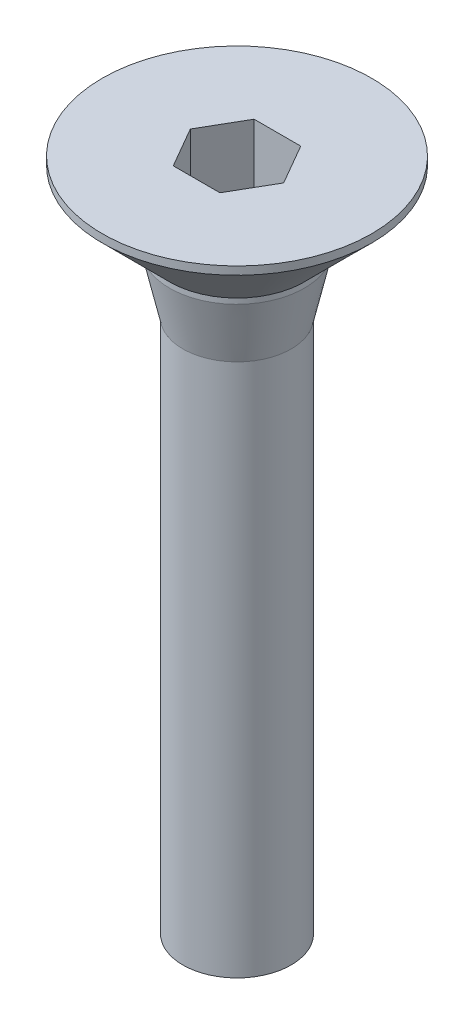
SolidWorks part; units mm, degrees
ref_plane "Vorne" through (0, 0, 0) normal (0, 0, 1) x (1, 0, 0)
ref_plane "Oben" through (0, 0, 0) normal (0, 1, 0) x (1, 0, 0)
ref_plane "Rechts" through (0, 0, 0) normal (1, 0, 0) x (0, 0, -1)
sketch "Skizze1" plane through (0, 0, 0) normal (0, 0, 1) x (1, 0, 0)
  line L0 (0, 0) -> (5, 0)
  line L1 (5, 0) -> (5, -0.3)
  line L2 (5, -0.3) -> (2.5, -2.8)
  line L3 (2.5, -2.8) -> (2.5, -3)
  line L4 (2.5, -3) -> (2.0095, -5.2)
  line L5 (2.0095, -5.2) -> (2.0095, -25)
  line L6 (2.0095, -25) -> (0, -25)
  line L7 (0, -25) -> (0, 0)
  line L8 (0, 0) -> (0, -25) construction
  dimension "DK" = 4.019
  dimension "D2" = 45
  dimension "DG" = 5
  dimension "DA" = 10
  dimension "K" = 2.8
  dimension "LS" = 3
  dimension "LG" = 5.2
  dimension "L" = 25
revolve "Basis-Rotation" add sketch "Skizze1" angle 360 about L8
sketch "Skizze2" plane through (0, 0, 0) normal (0, 1, 0) x (-1, 0, 0)
  line L0 (1.7321, 0) -> (-1.7321, 0) construction
  line L1 (0, 1.5) -> (0, -1.5) construction
  line L2 (0.866, -1.5) -> (-0.866, -1.5)
  line L3 (-0.866, -1.5) -> (-1.7321, 0)
  line L4 (0.866, -1.5) -> (1.7321, 0)
  line L5 (0.866, 1.5) -> (1.7321, 0)
  line L6 (-0.866, 1.5) -> (-1.7321, 0)
  line L7 (0.866, 1.5) -> (-0.866, 1.5)
  dimension "D2" = 120
extrude "Schnitt-Linear austragen1" cut sketch "Skizze2" against normal blind 5.3
